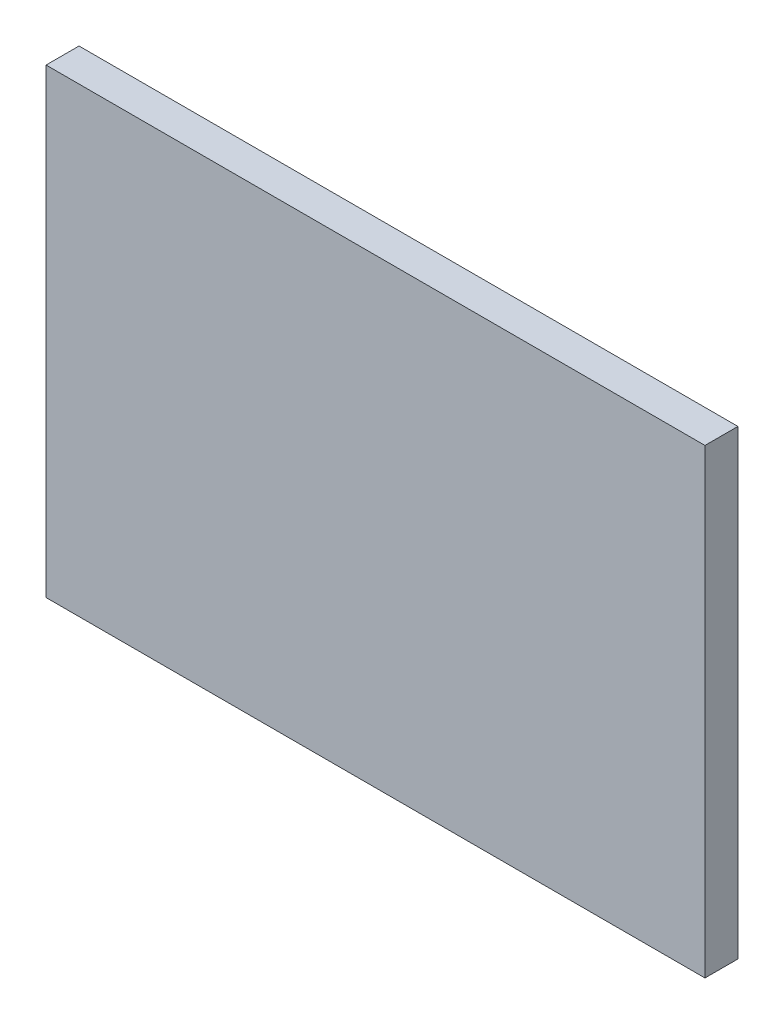
SolidWorks part; units mm, degrees
ref_plane "Plan de face" through (0, 0, 0) normal (0, 0, 1) x (1, 0, 0)
ref_plane "Plan de dessus" through (0, 0, 0) normal (0, 1, 0) x (1, 0, 0)
ref_plane "Plan de droite" through (0, 0, 0) normal (1, 0, 0) x (0, 0, -1)
sketch "Esquisse1" plane through (0, 0, 0) normal (0, 0, 1) x (1, 0, 0)
  line L1 (-20, 14) -> (20, 14)
  line L2 (-20, 14) -> (-20, -14)
  line L3 (-20, -14) -> (20, -14)
  line L4 (20, 14) -> (20, -14)
  line L5 (-20, 14) -> (20, -14) construction
  line L6 (-20, -14) -> (20, 14) construction
  point P0 (0, 0)
  dimension "D1" = 28
  dimension "D2" = 40
extrude "Boss.-Extru.1" add sketch "Esquisse1" along normal blind 2
